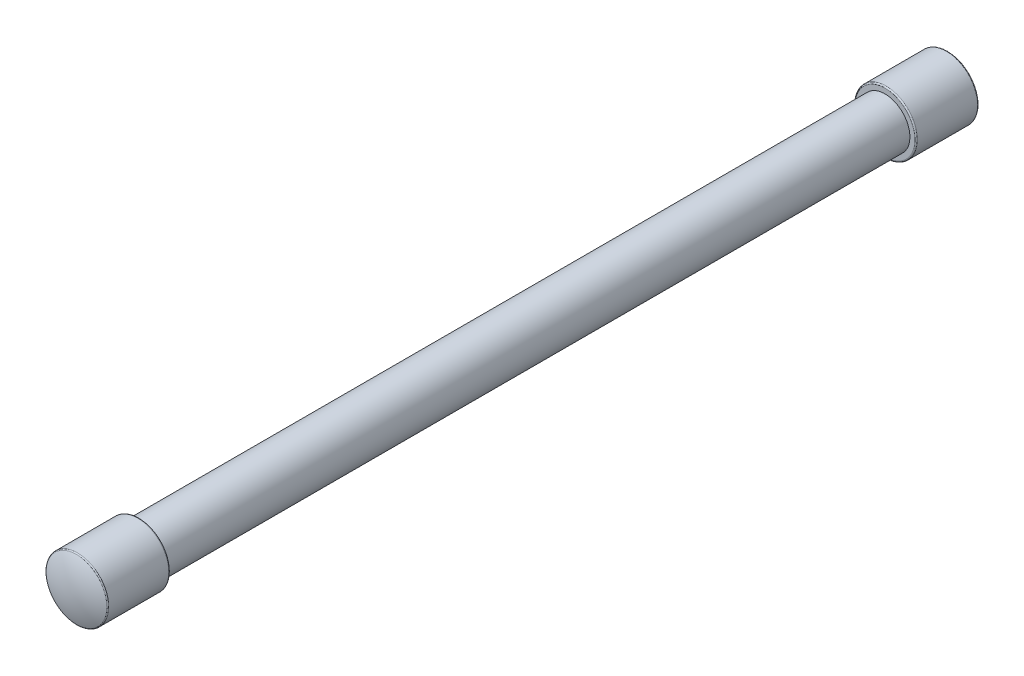
SolidWorks part; units mm, degrees
ref_plane "Front Plane" through (0, 0, 0) normal (0, 0, 1) x (1, 0, 0)
ref_plane "Top Plane" through (0, 0, 0) normal (0, 1, 0) x (1, 0, 0)
ref_plane "Right Plane" through (0, 0, 0) normal (1, 0, 0) x (0, 0, -1)
sketch "Sketch1" plane through (0, 0, 0) normal (1, 0, 0) x (0, 0, -1)
  line L0 (0, 0) -> (71.0913, 0)
  line L1 (0, 0) -> (0, 4)
  line L2 (0, 4) -> (60, 4)
  line L3 (60, 4) -> (60, 5)
  line L4 (60, 5) -> (70, 5)
  line L5 (71.0913, 0) -> (71.0913, 18.7777) construction
  arc A0 (70, 5) -> (71.0913, 0) centre (59.0913, 0) cw
  dimension "D5" = 12
  dimension "D1" = 60
  dimension "D2" = 10
  dimension "D3" = 4
  dimension "D4" = 5
revolve "Revolve1" add sketch "Sketch1" angle 360 about L0
mirror "Mirror1" about plane through (0, 0, 0) normal (0, 0, 1) of bodies 101
fillet "Fillet1" radius 0.2 4 edges at (5, 0, -70) (5, 0, -60) (5, 0, 70) (5, 0, 60)
